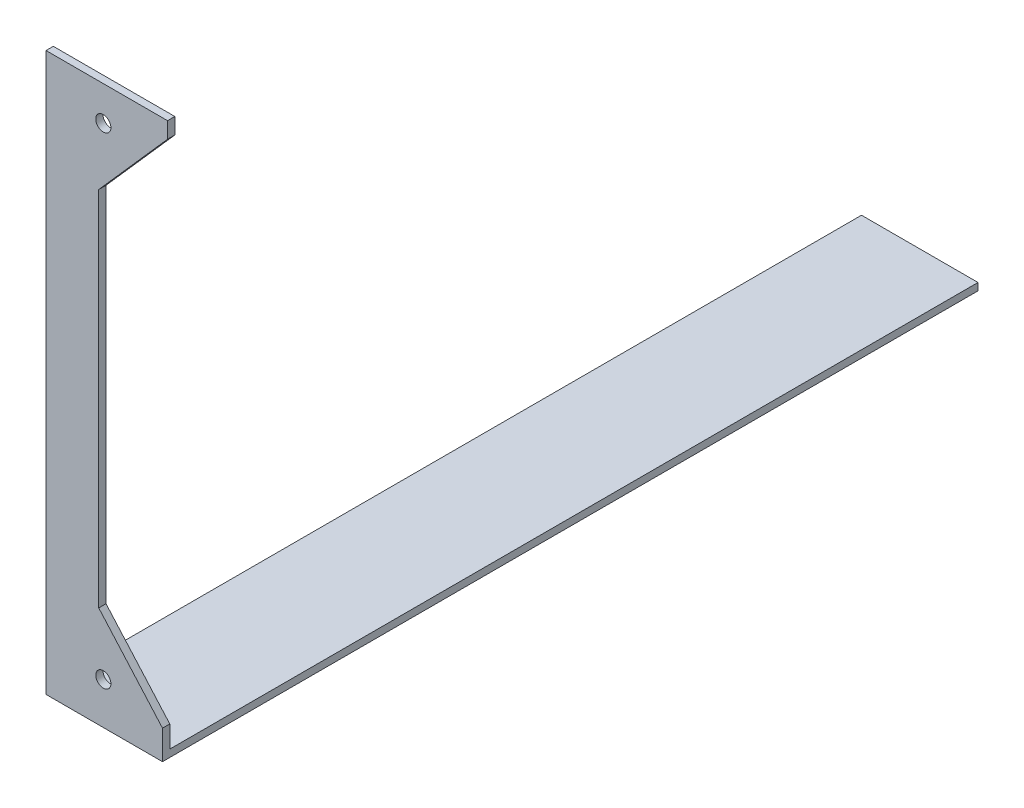
SolidWorks part; units mm, degrees
ref_plane "Front Plane" through (0, 0, 0) normal (0, 0, 1) x (1, 0, 0)
ref_plane "Top Plane" through (0, 0, 0) normal (0, 1, 0) x (1, 0, 0)
ref_plane "Right Plane" through (0, 0, 0) normal (1, 0, 0) x (0, 0, -1)
sketch "Sketch1" plane through (0, 0, 0) normal (0, 0, 1) x (1, 0, 0)
  line L0 (-250, 120) -> (0, 120) construction
  line L1 (-238.5, 99.5) -> (-223.5, 116.5) construction
  line L2 (-244.6, 99.5) -> (-238.5, 99.5) construction
  line L3 (-244.6, 20.5) -> (-244.6, 99.5) construction
  line L4 (-250, 2) -> (-250, 118) construction
  line L5 (0, 0) -> (-250, 0) construction
  line L6 (-238.5, 20.5) -> (-244.6, 20.5) construction
  line L7 (-223.5, 3.5) -> (-238.5, 20.5) construction
  line L8 (-250, 120) -> (-223.5, 120)
  line L9 (-238.5, 99.5) -> (-223.5, 116.5)
  line L10 (-244.6, 99.5) -> (-238.5, 99.5)
  line L11 (-244.6, 20.5) -> (-244.6, 99.5)
  line L12 (-250, 0) -> (-250, 120)
  line L13 (-223.5, 0) -> (-250, 0)
  line L14 (-238.5, 20.5) -> (-244.6, 20.5)
  line L15 (-223.5, 3.5) -> (-238.5, 20.5)
  line L16 (-223.5, 116.5) -> (-223.5, 120)
  line L17 (-223.5, 3.5) -> (-223.5, 0)
  line L18 (-238.5, 20.5) -> (-238.5, 99.5)
  line L19 (-224.6, 4.7467) -> (-224.6, 0)
  arc A0 (-239.15, 112.5) -> (-235.85, 112.5) centre (-237.5, 112.5) ccw construction
  arc A1 (-235.85, 112.5) -> (-239.15, 112.5) centre (-237.5, 112.5) ccw construction
  arc A2 (-235.85, 7.5) -> (-239.15, 7.5) centre (-237.5, 7.5) ccw construction
  arc A3 (-239.15, 7.5) -> (-235.85, 7.5) centre (-237.5, 7.5) ccw construction
  arc A4 (-239.15, 112.5) -> (-235.85, 112.5) centre (-237.5, 112.5) ccw
  arc A5 (-235.85, 112.5) -> (-239.15, 112.5) centre (-237.5, 112.5) ccw
  arc A6 (-235.85, 7.5) -> (-239.15, 7.5) centre (-237.5, 7.5) ccw
  arc A7 (-239.15, 7.5) -> (-235.85, 7.5) centre (-237.5, 7.5) ccw
  dimension "D1" = 25.4
extrude "Boss-Extrude1" add sketch "Sketch1" along normal blind 1.5875 contours L14 L18 L10 L11 | L17 L15 L14 L11 L10 L9 L16 L8 L12 L13 A7 A6 A5 A4
sketch "Sketch2" plane through (0, 0, 0) normal (0, 1, 0) x (1, 0, 0)
  line L1 (-250, -1.5875) -> (-250, 176.2125)
  line L2 (-250, 176.2125) -> (-224.6, 176.2125)
  line L3 (-224.6, 176.2125) -> (-224.6, -1.5875)
  line L4 (-224.6, -1.5875) -> (-250, -1.5875) construction
  line L5 (-224.6, -1.5875) -> (-250, -1.5875)
  dimension "D1" = 177.8
extrude "Boss-Extrude2" add sketch "Sketch2" against normal blind 1.5875 contours L3 L5 L1 L2
